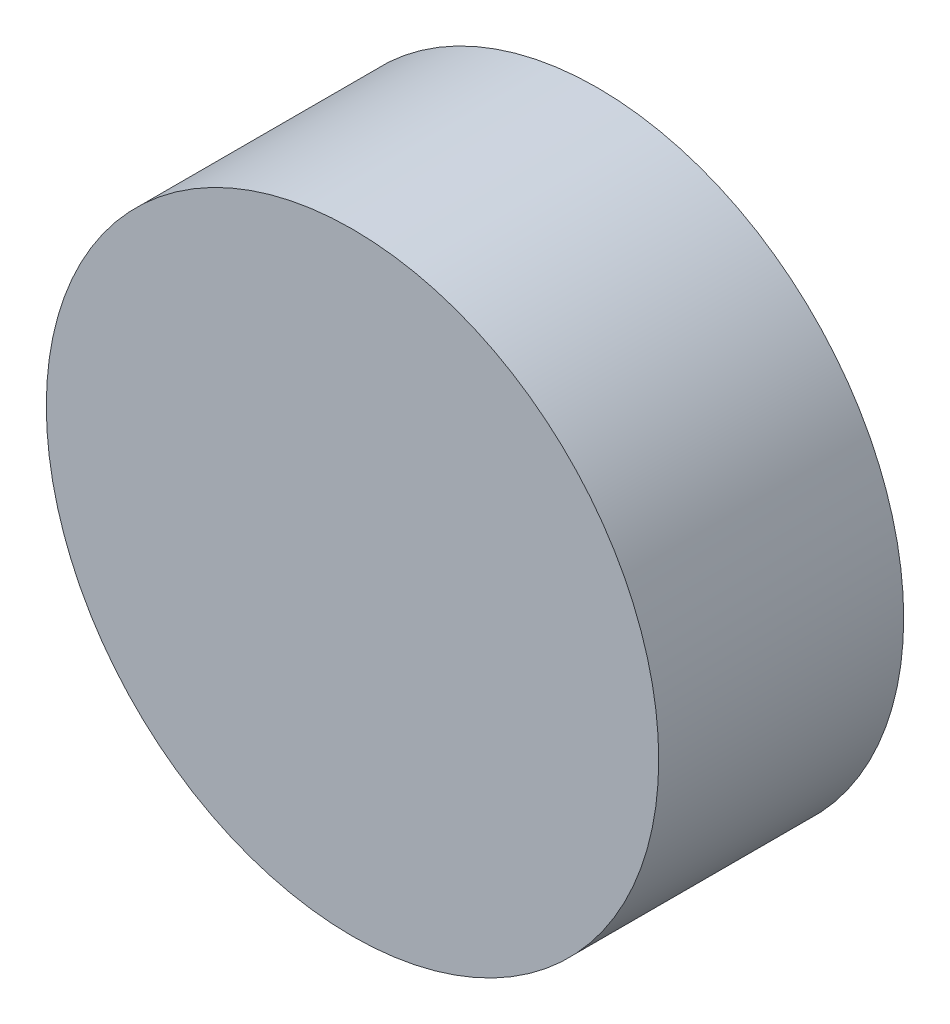
SolidWorks part; units mm, degrees
ref_plane "Plan de face" through (0, 0, 0) normal (0, 0, 1) x (1, 0, 0)
ref_plane "Plan de dessus" through (0, 0, 0) normal (0, 1, 0) x (1, 0, 0)
ref_plane "Plan de droite" through (0, 0, 0) normal (1, 0, 0) x (0, 0, -1)
sketch "Esquisse1" plane through (0, 0, 0) normal (0, 0, 1) x (1, 0, 0)
  circle A0 centre (0, 0) radius 2.5
  dimension "D1" = 5
extrude "Boss.-Extru.1" add sketch "Esquisse1" along normal blind 2 contours A0
